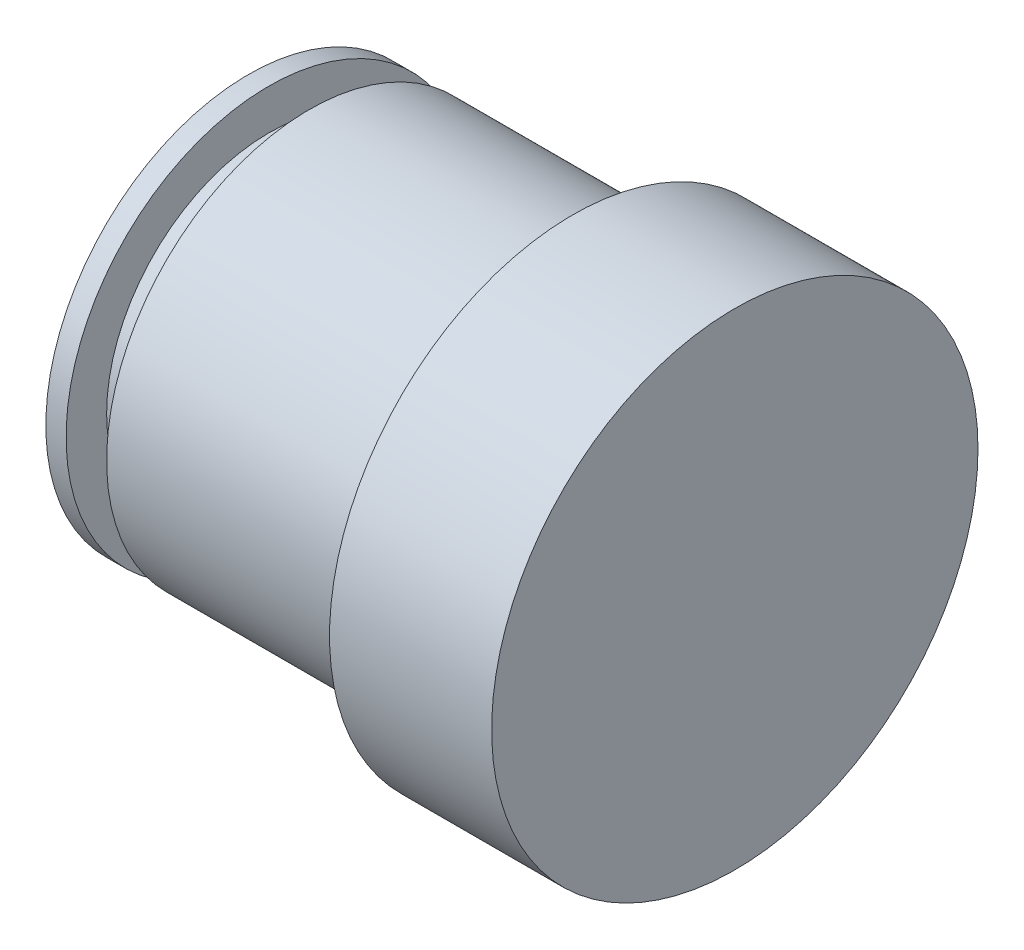
SolidWorks part; units mm, degrees
ref_plane "Front Plane" through (0, 0, 0) normal (0, 0, 1) x (1, 0, 0)
ref_plane "Top Plane" through (0, 0, 0) normal (0, 1, 0) x (1, 0, 0)
ref_plane "Right Plane" through (0, 0, 0) normal (1, 0, 0) x (0, 0, -1)
sketch "Sketch1" plane through (0, 0, 0) normal (0, 1, 0) x (1, 0, 0)
  line L0 (0, 0) -> (0, 5)
  line L3 (0.5, 5) -> (0.5, 4)
  line L4 (0.5, 4) -> (1.5, 4)
  line L5 (1.5, 4) -> (1.5, 5)
  line L6 (1.5, 5) -> (7.5, 5)
  line L7 (8, 5.5) -> (8, 6)
  line L8 (8, 6) -> (12, 6)
  line L9 (12, 6) -> (12, 0)
  line L10 (12, 0) -> (0, 0)
  line L11 (0, 5) -> (0.5, 5)
  arc A0 (8, 5.5) -> (7.5, 5) centre (7.5, 5.5) cw
  dimension "D3" = 0.5
  dimension "D1" = 1
  dimension "D2" = 12
  dimension "D4" = 4
  dimension "D5" = 8
  dimension "D6" = 0.5
  dimension "D7" = 5
  dimension "D8" = 6
revolve "Revolve1" add sketch "Sketch1" angle 360 about L10
